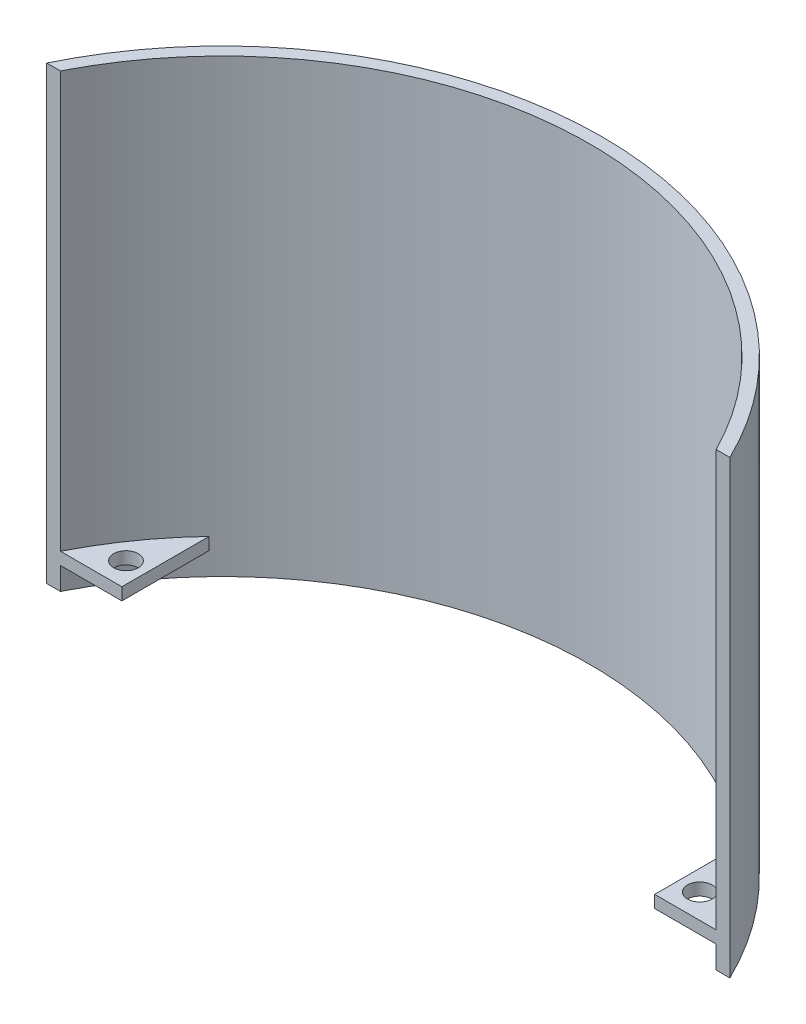
SolidWorks part; units mm, degrees
ref_plane "Front Plane" through (0, 0, 0) normal (0, 0, 1) x (1, 0, 0)
ref_plane "Top Plane" through (0, 0, 0) normal (0, 1, 0) x (1, 0, 0)
ref_plane "Right Plane" through (0, 0, 0) normal (1, 0, 0) x (0, 0, -1)
sketch "Sketch1" plane through (0, 0, 0) normal (0, 1, 0) x (1, 0, 0)
  line L0 (-80, 40.4835) -> (80, 40.4835) construction
  line L1 (-106.2568, 40.4835) -> (107.37, 40.4835) construction
  line L2 (-80, 40.4835) -> (-83.3484, 40.4835)
  line L3 (80, 40.4835) -> (83.3484, 40.4835)
  arc A0 (-80, 40.4835) -> (80, 40.4835) centre (0, 0) cw
  arc A1 (-83.3484, 40.4835) -> (83.3484, 40.4835) centre (0, 0) cw
  dimension "D2" = 89.66
  dimension "D3" = 3
  dimension "D1" = 160
extrude "Boss-Extrude1" add sketch "Sketch1" along normal blind 110
sketch "Sketch2" plane through (0, 0, 0) normal (0, 1, 0) x (1, 0, 0)
  line L0 (-80, 40.4835) -> (-65, 40.4835)
  line L1 (-65, 40.4835) -> (-65, 61.7569)
  line L2 (80, 40.4835) -> (65, 40.4835)
  line L3 (65, 40.4835) -> (65, 61.7569)
  arc A0 (80, 40.4835) -> (-80, 40.4835) centre (0, 0) ccw construction
  arc A1 (80, 40.4835) -> (65, 61.7569) centre (0, 0) ccw
  arc A2 (-65, 61.7569) -> (-80, 40.4835) centre (0, 0) ccw
  circle A3 centre (-70, 46.4835) radius 3
  circle A4 centre (70, 46.4835) radius 3
  dimension "D3" = 6
  dimension "D4" = 6
  dimension "D1" = 15
  dimension "D2" = 15
  dimension "D5" = 10
  dimension "D6" = 6
  dimension "D7" = 10
  dimension "D8" = 6
extrude "Boss-Extrude2" add sketch "Sketch2" along normal blind 3 from offset 5.5
